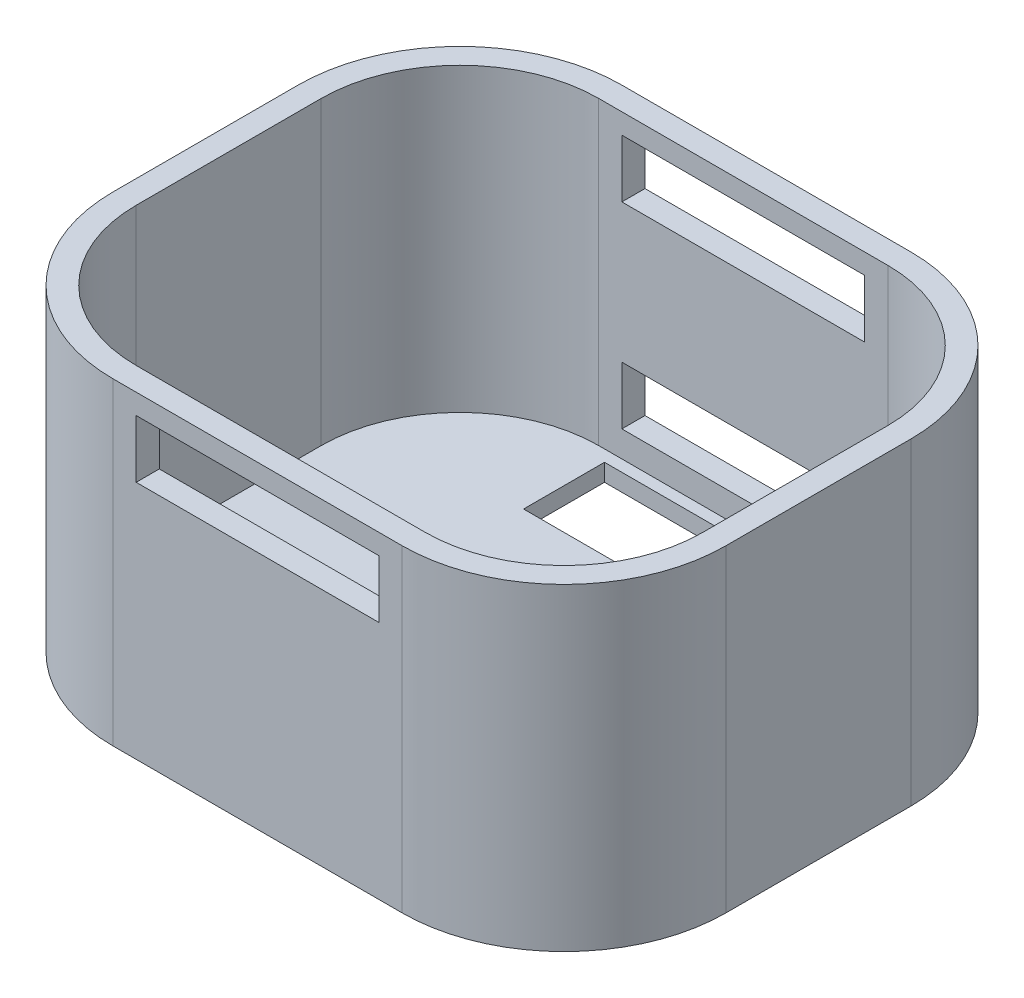
SolidWorks part; units mm, degrees
ref_plane "Front Plane" through (0, 0, 0) normal (0, 0, 1) x (1, 0, 0)
ref_plane "Top Plane" through (0, 0, 0) normal (0, 1, 0) x (1, 0, 0)
ref_plane "Right Plane" through (0, 0, 0) normal (1, 0, 0) x (0, 0, -1)
sketch "Sketch1" plane through (0, 0, 0) normal (0, 1, 0) x (1, 0, 0)
  line L0 (12.5, 22) -> (-12.5, 22) construction
  line L1 (12.5, -20) -> (-12.5, -20)
  line L2 (24.5, -8) -> (24.5, 8)
  line L3 (12.5, 20) -> (-12.5, 20)
  line L4 (-24.5, -8) -> (-24.5, 8)
  line L5 (24.5, -20) -> (-24.5, 20) construction
  line L6 (24.5, 20) -> (-24.5, -20) construction
  line L7 (26.5, -8) -> (26.5, 8) construction
  line L8 (12.5, -22) -> (-12.5, -22) construction
  line L9 (-26.5, -8) -> (-26.5, 8) construction
  line L10 (-26.5, 8) -> (-26.5, -8)
  line L11 (-12.5, -22) -> (12.5, -22)
  line L12 (26.5, -8) -> (26.5, 8)
  line L13 (12.5, 22) -> (-12.5, 22)
  arc A0 (12.5, 20) -> (24.5, 8) centre (12.5, 8) cw
  arc A1 (24.5, -8) -> (12.5, -20) centre (12.5, -8) cw
  arc A2 (-12.5, -20) -> (-24.5, -8) centre (-12.5, -8) cw
  arc A3 (-24.5, 8) -> (-12.5, 20) centre (-12.5, 8) cw
  arc A4 (-26.5, 8) -> (-12.5, 22) centre (-12.5, 8) cw construction
  arc A5 (12.5, 22) -> (26.5, 8) centre (12.5, 8) cw construction
  arc A6 (26.5, -8) -> (12.5, -22) centre (12.5, -8) cw construction
  arc A7 (-12.5, -22) -> (-26.5, -8) centre (-12.5, -8) cw construction
  arc A8 (-12.5, 22) -> (-26.5, 8) centre (-12.5, 8) ccw
  arc A9 (-26.5, -8) -> (-12.5, -22) centre (-12.5, -8) ccw
  arc A10 (12.5, -22) -> (26.5, -8) centre (12.5, -8) ccw
  arc A11 (26.5, 8) -> (12.5, 22) centre (12.5, 8) ccw
  point P0 (0, 0)
  point P33 (26.5, 0)
  point P43 (-26.5, 0)
  point P44 (0, 22)
  dimension "D3" = 12
  dimension "D1" = 53
  dimension "D2" = 44
  dimension "D5" = 16
  dimension "D4" = 2
extrude "Boss-Extrude1" add sketch "Sketch1" along normal mid plane 27.5
sketch "Sketch2" plane through (0, 0, -20) normal (0, 0, 1) x (1, 0, 0)
  line L0 (-26.5, 0) -> (26.5, 0) construction
  line L1 (-10.5, 12) -> (10.5, 12)
  line L2 (-10.5, 12) -> (-10.5, 7)
  line L3 (-10.5, 7) -> (10.5, 7)
  line L4 (10.5, 12) -> (10.5, 7)
  line L5 (-10.5, 12) -> (10.5, 7) construction
  line L6 (-10.5, 7) -> (10.5, 12) construction
  line L9 (-26.5, 13.75) -> (-26.5, -13.75) construction
  line L10 (26.5, 13.75) -> (26.5, -13.75) construction
  line L11 (0, 13.75) -> (0, -13.75) construction
  line L12 (-12.5, 13.75) -> (12.5, 13.75) construction
  line L13 (-12.5, -13.75) -> (12.5, -13.75) construction
  point P0 (0, 9.5)
  dimension "D1" = 21
  dimension "D2" = 5
  dimension "D3" = 9.5
extrude "Cut-Extrude1" cut sketch "Sketch2" against normal through all both and the other way through all
sketch "Sketch3" plane through (0, -13.75, 0) normal (0, -1, 0) x (1, 0, 0)
  line L4 (-12.5, -22) -> (12.5, -22)
  line L5 (26.5, -8) -> (26.5, 8)
  line L12 (12.5, 22) -> (-12.5, 22)
  line L13 (-26.5, 8) -> (-26.5, -8)
  line L14 (-12.5, -22) -> (12.5, -22)
  line L15 (26.5, -8) -> (26.5, 8)
  line L16 (12.5, 22) -> (-12.5, 22)
  line L17 (-26.5, 8) -> (-26.5, -8)
  arc A12 (-26.5, -8) -> (-12.5, -22) centre (-12.5, -8) ccw
  arc A13 (12.5, -22) -> (26.5, -8) centre (12.5, -8) ccw
  arc A14 (26.5, 8) -> (12.5, 22) centre (12.5, 8) ccw
  arc A15 (-12.5, 22) -> (-26.5, 8) centre (-12.5, 8) ccw
  arc A16 (-26.5, -8) -> (-12.5, -22) centre (-12.5, -8) ccw
  arc A17 (12.5, -22) -> (26.5, -8) centre (12.5, -8) ccw
  arc A18 (26.5, 8) -> (12.5, 22) centre (12.5, 8) ccw
  arc A19 (-12.5, 22) -> (-26.5, 8) centre (-12.5, 8) ccw
  dimension "D1" = 0
extrude "Boss-Extrude2" add sketch "Sketch3" against normal blind 1.5
sketch "Sketch4" plane through (0, 0, -22) normal (0, 0, -1) x (-1, 0, 0)
  line L5 (-10.5, -5) -> (10.5, -5)
  line L6 (-10.5, -5) -> (-10.5, -10)
  line L7 (-10.5, -10) -> (10.5, -10)
  line L9 (10.5, -5) -> (10.5, -10)
  line L10 (-10.5, -5) -> (10.5, -10) construction
  line L11 (-10.5, -10) -> (10.5, -5) construction
  point P0 (0, -7.5)
  dimension "D1" = 5
  dimension "D2" = 21
  dimension "D3" = 7.5
extrude "Cut-Extrude2" cut sketch "Sketch4" against normal blind 2
sketch "Sketch5" plane through (0, -12.25, 0) normal (0, 1, 0) x (-1, 0, 0)
  line L0 (-24.3987, 0) -> (22.5042, 0) construction
  line L5 (-11, 19) -> (11, 12) construction
  line L6 (-11, 12) -> (11, 19) construction
  line L7 (-11, -12) -> (11, -12)
  line L8 (11, -19) -> (11, -12)
  line L9 (-11, -19) -> (11, -19)
  line L10 (-11, -19) -> (-11, -12)
  point P0 (0, 15.5)
  dimension "D1" = 7
  dimension "D2" = 22
  dimension "D3" = 15.5
extrude "Cut-Extrude3" cut sketch "Sketch5" against normal blind 2
